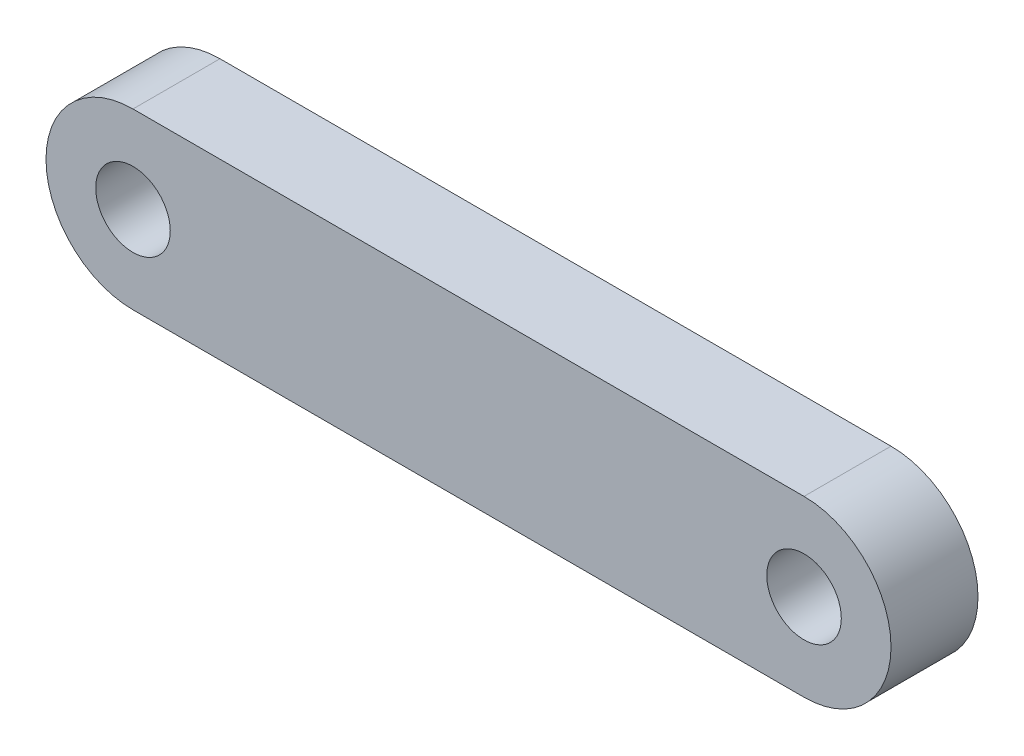
SolidWorks part; units mm, degrees
ref_plane "Front Plane" through (0, 0, 0) normal (0, 0, 1) x (1, 0, 0)
ref_plane "Top Plane" through (0, 0, 0) normal (0, 1, 0) x (1, 0, 0)
ref_plane "Right Plane" through (0, 0, 0) normal (1, 0, 0) x (0, 0, -1)
sketch "Sketch1" plane through (0, 0, 0) normal (0, 0, 1) x (1, 0, 0)
  line L0 (0, 0) -> (27, 0)
  line L5 (0, -7) -> (27, -7)
  arc A8 (27, 0) -> (27, -7) centre (27, -3.5) cw
  arc A9 (0, -7) -> (0, 0) centre (0, -3.5) cw
  circle A10 centre (0, -3.5) radius 1.5
  circle A11 centre (27, -3.5) radius 1.5
  dimension "D1" = 3
  dimension "D2" = 3
  dimension "D3" = 2
  dimension "D4" = 27
  dimension "D5" = 2
extrude "Boss-Extrude1" add sketch "Sketch1" along normal blind 3.5
